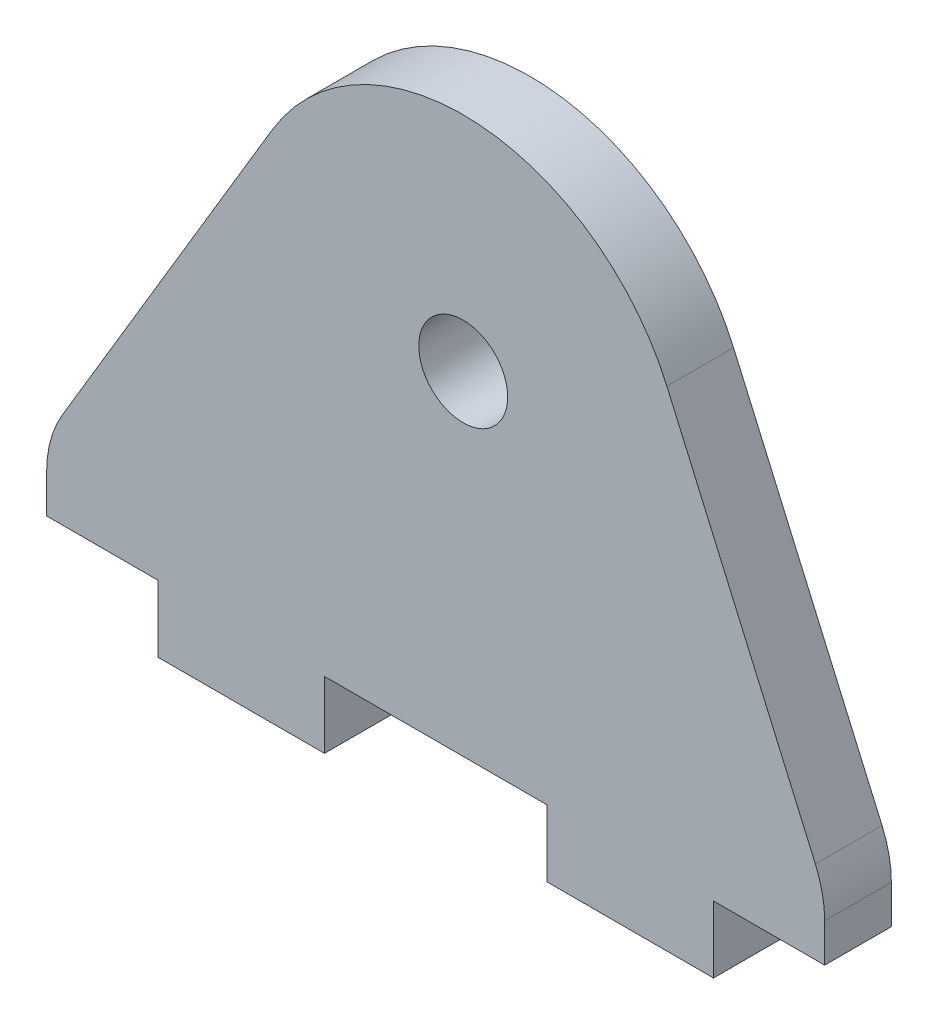
SolidWorks part; units mm, degrees
ref_plane "Plan de face" through (0, 0, 0) normal (0, 0, 1) x (1, 0, 0)
ref_plane "Plan de dessus" through (0, 0, 0) normal (0, 1, 0) x (1, 0, 0)
ref_plane "Plan de droite" through (0, 0, 0) normal (1, 0, 0) x (0, 0, -1)
sketch "Esquisse1" plane through (0, 0, 0) normal (0, 0, 1) x (1, 0, 0)
  line L0 (-13.4045, 2.5938) -> (1.5955, 2.5938)
  line L1 (1.5955, 2.5938) -> (1.5955, 8.5938)
  line L2 (1.5955, 8.5938) -> (21.5955, 8.5938)
  line L3 (21.5955, 8.5938) -> (21.5955, 2.5938)
  line L4 (21.5955, 2.5938) -> (36.5955, 2.5938)
  line L5 (36.5955, 2.5938) -> (36.5955, 8.5938)
  line L6 (36.5955, 8.5938) -> (46.5955, 8.5938)
  line L7 (46.5955, 8.5938) -> (46.5955, 12.0485)
  line L8 (45.7578, 16.055) -> (32.3981, 46.6068)
  line L9 (-3.1029, 48.8394) -> (-21.9927, 17.1713)
  line L10 (-23.4045, 12.0485) -> (-23.4045, 8.5938)
  line L11 (-23.4045, 8.5938) -> (-13.4045, 8.5938)
  line L12 (-13.4045, 8.5938) -> (-13.4045, 2.5938)
  line L13 (46.5955, 12.0485) -> (-23.4045, 12.0485) construction
  arc A0 (32.3981, 46.6068) -> (-3.1029, 48.8394) centre (14.0735, 38.5938) ccw
  arc A1 (46.5955, 12.0485) -> (45.7578, 16.055) centre (36.5955, 12.0485) ccw
  arc A2 (-21.9927, 17.1713) -> (-23.4045, 12.0485) centre (-13.4045, 12.0485) ccw
  circle A3 centre (14.0735, 38.5938) radius 4
  point P20 (-23.4045, 12.1136)
  dimension "D6" = 20
  dimension "D7" = 10
  dimension "D9" = 8
  dimension "D1" = 70
  dimension "D2" = 6
  dimension "D3" = 15
  dimension "D4" = 10
  dimension "D5" = 10
  dimension "D8" = 30
extrude "Boss.-Extru.1" add sketch "Esquisse1" along normal blind 6
